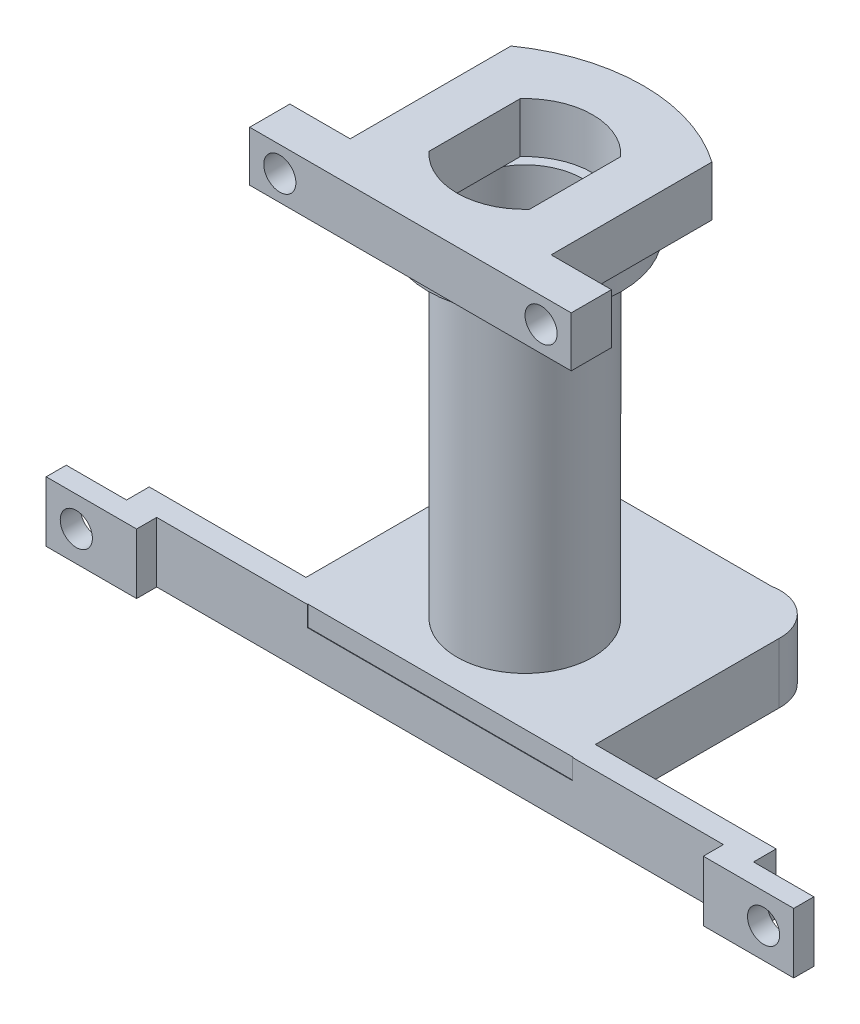
SolidWorks part; units mm, degrees
ref_plane "Front Plane" through (0, 0, 0) normal (0, 0, 1) x (1, 0, 0)
ref_plane "Top Plane" through (0, 0, 0) normal (0, 1, 0) x (1, 0, 0)
ref_plane "Right Plane" through (0, 0, 0) normal (1, 0, 0) x (0, 0, -1)
sketch "Sketch1" plane through (0, 0, 0) normal (0, 1, 0) x (1, 0, 0)
  line L0 (0, 0) -> (20, 0)
  line L1 (20, 0) -> (20, 20)
  line L2 (20, 20) -> (20, 0)
  line L3 (0, 0) -> (0, 20)
  line L4 (5, 18.8941) -> (5, 4)
  line L5 (5, 4) -> (15, 4)
  line L6 (15, 4) -> (15, 18.7765)
  line L7 (20, 4) -> (26, 4)
  line L8 (26, 4) -> (26, 0)
  line L9 (26, 0) -> (20, 0)
  line L10 (0, 4) -> (-6, 4)
  line L11 (-6, 4) -> (-6, 0)
  line L12 (-6, 0) -> (0, 0)
  arc A0 (0, 20) -> (20, 20) centre (10, 5.828) cw
  arc A1 (5, 18.8941) -> (15, 18.7765) centre (9.8607, 6.996) cw
  dimension "D6" = 12.8527
  dimension "D7" = 17.3449
  dimension "D1" = 5
  dimension "D2" = 5
  dimension "D3" = 20
  dimension "D4" = 20
  dimension "D5" = 4
  dimension "D8" = 20
  dimension "D9" = 14.7765
  dimension "D10" = 14.8941
  dimension "D11" = 6
  dimension "D12" = 6
extrude "Boss-Extrude1" add sketch "Sketch1" along normal blind 5 contours A0 L3 L0 L1 L4 A1 L6 L5 | L11 L12 L3 L10 | L9 L8 L7 L1
sketch "Sketch2" plane through (0, 0, -4) normal (0, 0, -1) x (-1, 0, 0)
  circle A0 centre (3, 2.5) radius 1.6
  circle A1 centre (-23, 2.5) radius 1.6
  dimension "D1" = 3.2
  dimension "D2" = 3.2
extrude "Cut-Extrude1" cut sketch "Sketch2" against normal blind 5
sketch "Sketch4" plane through (0, 5, 0) normal (0, 1, 0) x (1, 0, 0)
  line L0 (5, 4) -> (15, 4) construction
  line L1 (15, 4) -> (15, 18.7765) construction
  circle A0 centre (10, 11.3882) radius 9.6542
  circle A1 centre (10, 11.3882) radius 6.7522
extrude "Boss-Extrude3" add sketch "Sketch4" against normal blind 7
sketch "Sketch5" plane through (0, 0, 0) normal (0, -1, 0) x (1, 0, 0)
  circle A0 centre (10, -11.3882) radius 6.7522
  circle A1 centre (10, -11.3882) radius 5.75
  dimension "D1" = 11.5
extrude "Boss-Extrude4" add sketch "Sketch5" along normal blind 35
sketch "Sketch7" plane through (0, -35, 0) normal (0, -1, 0) x (1, 0, 0)
  line L0 (0, -24) -> (19.819, -24)
  line L1 (22, -22.281) -> (22, -4)
  line L3 (20, -4) -> (26, -4) construction
  line L5 (0, -4) -> (0, -20) construction
  line L6 (20, -4) -> (20, -20) construction
  line L7 (-2, -22.281) -> (-2, -4)
  line L8 (0, -4) -> (-6, -4) construction
  line L9 (-6, 0) -> (26, 0) construction
  line L10 (24.4, -4) -> (24.4, -22.281)
  line L11 (19.5508, -26.4) -> (-0.2682, -26.4)
  line L12 (-4.5046, -4) -> (-4.4, -4)
  line L13 (-4.4, -4) -> (-4.4, -22.281)
  line L14 (24.4, -4) -> (22, -4)
  line L15 (-2, -4) -> (-4.4, -4)
  arc A0 (22, -22.281) -> (19.819, -24) centre (20.05, -22.05) cw
  arc A1 (-2, -22.281) -> (0, -24) centre (-0.1405, -22.1405) ccw
  arc A2 (24.4, -22.281) -> (19.5508, -26.4) centre (20.3427, -22.4184) cw
  arc A3 (-0.2682, -26.4) -> (-4.4, -22.281) centre (-0.4249, -22.4253) cw
  dimension "D1" = 2
  dimension "D2" = 2
  dimension "D3" = 24
  dimension "D4" = 2.4
  dimension "D5" = 2.4
  dimension "D6" = 2.4
extrude "Boss-Extrude5" add sketch "Sketch7" along normal blind 6 separate body contours A3 L11 A2 L10 L14 L1 A0 L0 A1 L7 L15 L13
sketch "Sketch9" plane through (0, -35, 0) normal (0, -1, 0) x (1, 0, 0)
  line L0 (-4.4, -4) -> (-4.4, -22.281) construction
  line L1 (24.4, -4) -> (-4.4, -4)
  line L2 (24.4, -4) -> (24.4, -26.4)
  line L3 (24.4, -26.4) -> (-4.4, -26.4)
  line L4 (-4.4, -4) -> (-4.4, -26.4)
  circle A0 centre (10, -11.3882) radius 5.75
  arc A1 (-0.2682, -26.4) -> (-4.4, -22.5696) centre (-0.4249, -22.4253) cw
  arc A2 (-4.4, -22.281) -> (-0.2682, -26.4) centre (-0.4249, -22.4253) ccw construction
  arc A3 (19.5508, -26.4) -> (24.4, -22.281) centre (20.3427, -22.4184) ccw
  point P20 (0, 0)
  point P23 (0, 0)
  circle M2 centre (10, -11.3882) radius 6.7522
  dimension "D1" = 0
extrude "Boss-Extrude7" add sketch "Sketch9" along normal blind 2 contours L3 A3 L2 L1 L4 A1 M2
sketch "Sketch10" plane through (0, -37, 0) normal (0, -1, 0) x (1, 0, 0)
  line L0 (-2, -4) -> (-20, -4)
  line L1 (-20, -4) -> (-2, -4)
  line L2 (24.4, -4) -> (42.3959, -4)
  line L3 (-20, -4) -> (-20, -1.7449)
  line L4 (-20, -1.7449) -> (-24, -1.7449)
  line L5 (-24, -1.7449) -> (-24, 0.2551)
  line L6 (-24, 0.2551) -> (-17, 0.2551)
  line L7 (-17, 0.2551) -> (-17, -1.7449)
  line L8 (-17, -1.7449) -> (-2, -1.7449)
  line L9 (-2, -1.7449) -> (-2, -4)
  line L10 (24.4, -4) -> (24.4, -1.7449)
  line L11 (24.4, -1.7449) -> (39.4, -1.7449)
  line L12 (39.4, -1.7449) -> (39.4, 0.2551)
  line L13 (39.4, 0.2551) -> (46.4, 0.2551)
  line L14 (46.4, 0.2551) -> (46.4, -1.7449)
  line L15 (46.4, -1.7449) -> (42.3959, -1.7449)
  line L16 (42.3959, -1.7449) -> (42.3959, -4)
  dimension "D1" = 15
  dimension "D2" = 15
  dimension "D3" = 7
  dimension "D4" = 7
  dimension "D5" = 4.0041
  dimension "D6" = 4
  dimension "D7" = 2
  dimension "D8" = 2
  dimension "D9" = 2
  dimension "D10" = 2
extrude "Boss-Extrude8" add sketch "Sketch10" against normal blind 2 contours L9 L8 L7 L6 L5 L4 L3 L0 | L16 L15 L14 L13 L12 L11 L10 L2
sketch "Sketch11" plane through (0, 0, -4) normal (0, 0, 1) x (1, 0, 0)
  line L1 (-2, -35) -> (24.4, -35)
  line L2 (-2, -35) -> (-2, -37)
  line L3 (-2, -37) -> (24.4, -37)
  line L4 (24.4, -35) -> (24.4, -37)
extrude "Boss-Extrude9" add sketch "Sketch11" along normal blind 2.2
sketch "Sketch12" plane through (0, -37, 0) normal (0, -1, 0) x (1, 0, 0)
  line L0 (-20, -1.7449) -> (-24, -1.7449)
  line L1 (-24, -1.7449) -> (-24, 0.2551)
  line L2 (-24, 0.2551) -> (-17, 0.2551)
  line L3 (-17, 0.2551) -> (-17, -1.7449)
  line L4 (-17, -1.7449) -> (39.4, -1.7449)
  line L5 (39.4, -1.7449) -> (39.4, 0.2551)
  line L6 (39.4, 0.2551) -> (46.4, 0.2551)
  line L7 (46.4, 0.2551) -> (46.4, -1.7449)
  line L8 (46.4, -1.7449) -> (42.3959, -1.7449)
  line L9 (42.3959, -1.7449) -> (42.3959, -4)
  line L10 (42.3959, -4) -> (-20, -4)
  line L11 (-20, -4) -> (-20, -1.7449)
extrude "Boss-Extrude10" add sketch "Sketch12" along normal blind 4
sketch "Sketch13" plane through (46.4, 0, 0) normal (1, 0, 0) x (0, 0, -1)
  line L1 (-0.2551, -35) -> (1.7449, -35)
  line L2 (-0.2551, -35) -> (-0.2551, -41)
  line L3 (-0.2551, -41) -> (1.7449, -41)
  line L4 (1.7449, -35) -> (1.7449, -41)
extrude "Boss-Extrude11" add sketch "Sketch13" along normal blind 2
sketch "Sketch14" plane through (-24, 0, 0) normal (-1, 0, 0) x (0, 0, 1)
  line L1 (-1.7449, -35) -> (0.2551, -35)
  line L2 (-1.7449, -35) -> (-1.7449, -41)
  line L3 (-1.7449, -41) -> (0.2551, -41)
  line L4 (0.2551, -35) -> (0.2551, -41)
extrude "Boss-Extrude12" add sketch "Sketch14" along normal blind 2
sketch "Sketch15" plane through (0, 0, -1.7449) normal (0, 0, -1) x (-1, 0, 0)
  circle A0 centre (-45.3979, -38) radius 1.6
  circle A1 centre (23, -38) radius 1.6
  dimension "D1" = 3.2
  dimension "D2" = 3.2
extrude "Cut-Extrude2" cut sketch "Sketch15" against normal blind 2
